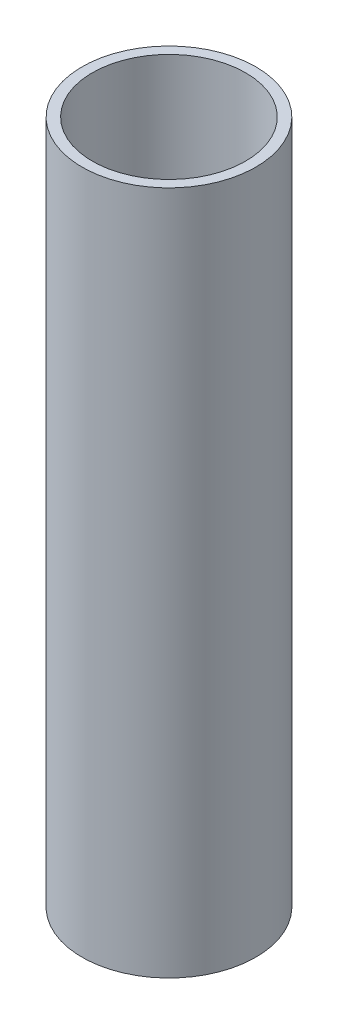
SolidWorks part; units mm, degrees
ref_plane "Front Plane" through (0, 0, 0) normal (0, 0, 1) x (1, 0, 0)
ref_plane "Top Plane" through (0, 0, 0) normal (0, 1, 0) x (1, 0, 0)
ref_plane "Right Plane" through (0, 0, 0) normal (1, 0, 0) x (0, 0, -1)
sketch "Sketch1" plane through (0, 0, 0) normal (0, 0, 1) x (1, 0, 0)
  line L0 (0, -200) -> (0, 100) construction
  line L1 (11.2, -100) -> (11.2, 0)
  line L2 (11.2, 0) -> (12.7, 0)
  line L3 (12.7, 0) -> (12.7, -100)
  line L4 (12.7, -100) -> (11.2, -100)
revolve "Revolve1" add sketch "Sketch1" angle 360 about L0
